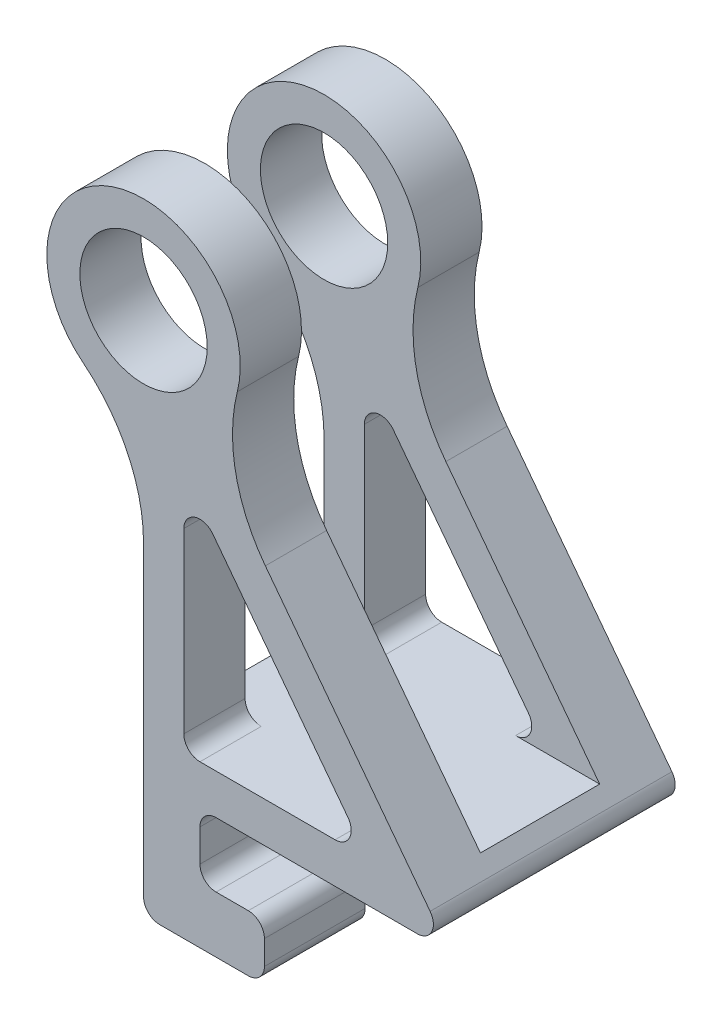
SolidWorks part; units mm, degrees
ref_plane "Front Plane" through (0, 0, 0) normal (1, 0, 0) x (0, 1, 0)
ref_plane "Top Plane" through (0, 0, 0) normal (0, 0, 1) x (0, 1, 0)
ref_plane "Right Plane" through (0, 0, 0) normal (0, 1, 0) x (-1, 0, 0)
sketch "Sketch1" plane through (0, 0, 0) normal (0, 0, 1) x (0, 1, 0)
  line L1 (0, -55) -> (0, 55) construction
  line L2 (0, 48.26) -> (63.5, 48.26)
  line L3 (63.5, 48.26) -> (0, 0)
  line L4 (0, 48.26) -> (-19.05, 48.26)
  line L5 (-19.05, 48.26) -> (-19.05, 29.21)
  line L6 (-19.05, 29.21) -> (0, 29.21)
  line L7 (0, 29.21) -> (0, 0)
  dimension "D1" = 48.26
  dimension "D2" = 63.5
  dimension "D3" = 19.05
  dimension "D4" = 19.05
extrude "Boss-Extrude1" add sketch "Sketch1" along normal blind 38.1
sketch "Sketch2" plane through (0, 0, 38.1) normal (0, 0, 1) x (0, -1, 0)
  circle A1 centre (-63.5, -48.26) radius 15.24
  dimension "D1" = 30.48
extrude "Boss-Extrude2" add sketch "Sketch2" against normal up to surface (38.1 mm away) up to face at (-30.988, 5.08, 0)
sketch "Sketch3" plane through (0, 0, 38.1) normal (0, 0, 1) x (1, 0, 0)
  line L0 (20.955, 0) -> (-20.955, 0) construction
  line L1 (-29.21, 0) -> (-39.37, 0)
  line L2 (-29.21, 0) -> (-29.21, -10.16)
  line L3 (-29.21, -10.16) -> (-39.37, -10.16)
  line L4 (-39.37, 0) -> (-39.37, -10.16)
  line L5 (-29.21, -19.05) -> (-29.21, 0) construction
  line L6 (-12.954, 6.35) -> (-41.91, 6.35)
  line L7 (-41.91, 6.35) -> (-41.91, 44.45)
  line L8 (-41.91, 44.45) -> (-12.954, 6.35)
  line L9 (-48.26, 48.26) -> (-48.26, -19.05) construction
  circle A0 centre (-48.26, 63.5) radius 10.033
  dimension "D7" = 20.066
  dimension "D1" = 10.16
  dimension "D2" = 10.16
  dimension "D3" = 6.35
  dimension "D4" = 6.35
  dimension "D5" = 38.1
  dimension "D6" = 28.956
extrude "Cut-Extrude1" cut sketch "Sketch3" against normal through all
fillet "Fillet9" radius 25.4 2 edges at (-39.0385, 51.3665, 19.05) (-48.26, 48.26, 19.05)
fillet "Fillet14" radius 2.54 3 edges at (-41.91, 6.35, 19.05) (-12.954, 6.35, 19.05) (-41.91, 44.45, 19.05)
fillet "Fillet15" radius 2.54 2 edges at (-39.37, 0, 19.05) (-39.37, -10.16, 19.05)
fillet "Fillet16" radius 2.54 1 edges at (-29.21, -10.16, 19.05)
fillet "Fillet17" radius 2.54 3 edges at (-48.26, -19.05, 19.05) (0, 0, 19.05) (-29.21, -19.05, 19.05)
sketch "Sketch4" plane through (0, -19.05, 0) normal (0, -1, 0) x (1, 0, 0)
  line L0 (-29.21, 38.1) -> (-29.21, 0) construction
  line L1 (-29.21, 22.225) -> (-39.37, 22.225)
  line L2 (-29.21, 22.225) -> (-29.21, 15.875)
  line L3 (-29.21, 15.875) -> (-39.37, 15.875)
  line L4 (-39.37, 22.225) -> (-39.37, 15.875)
  line L5 (-31.75, 0) -> (-31.75, 38.1) construction
  point P6 (-31.75, 19.05)
  point P7 (-31.75, 19.05)
  point P10 (-29.21, 19.05)
  dimension "D1" = 6.35
  dimension "D2" = 10.16
extrude "Cut-Extrude2" cut sketch "Sketch4" against normal up to next
sketch "Sketch6" plane through (0, 6.35, 0) normal (0, 1, 0) x (-1, 0, 0)
  line L1 (2.5807, 38.1) -> (2.5807, 0) construction
  line L3 (-10.3045, 28.448) -> (65.8955, 28.448)
  line L4 (-10.3045, 28.448) -> (-10.3045, 9.652)
  line L5 (-10.3045, 9.652) -> (65.8955, 9.652)
  line L6 (65.8955, 28.448) -> (65.8955, 9.652)
  point P0 (2.5807, 19.05)
  point P7 (-10.3045, 19.05)
  dimension "D1" = 18.796
  dimension "D2" = 76.2
extrude "Cut-Extrude3" cut sketch "Sketch6" along normal through all
equation "\"D4@Sketch1\"=\"D3@Sketch1\""
